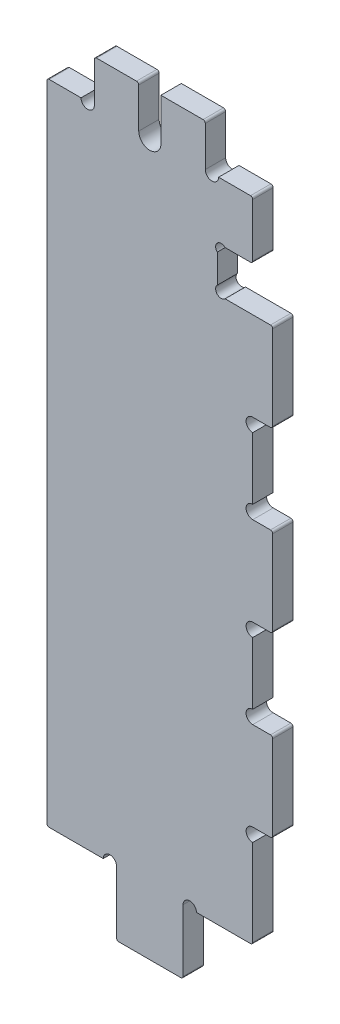
SolidWorks part; units mm, degrees
material "POM Acetal Copolymer"
ref_plane "Front Plane" through (0, 0, 0) normal (0, 0, 1) x (1, 0, 0)
ref_plane "Top Plane" through (0, 0, 0) normal (0, 1, 0) x (1, 0, 0)
ref_plane "Right Plane" through (0, 0, 0) normal (1, 0, 0) x (0, 0, -1)
sketch "Sketch1" plane through (0, 0, 0) normal (0, 0, 1) x (1, 0, 0)
  line L0 (10.7, 146) -> (10.7, 155.5)
  line L1 (0, 0) -> (15.7, 0)
  line L2 (0, 0) -> (0, 146)
  line L3 (0, 146) -> (10.7, 146)
  line L4 (46.4, 0) -> (46.4, 23)
  line L5 (10.7, 155.5) -> (20.7, 155.5)
  line L6 (20.7, 155.5) -> (20.7, 146)
  line L7 (20.7, 146) -> (25.7, 146)
  line L8 (10.7, 146) -> (20.7, 146) construction
  line L9 (23.2, -14.5) -> (23.2, 146) construction
  line L10 (15.7, 0) -> (15.7, -14.5)
  line L11 (15.7, -14.5) -> (30.7, -14.5)
  line L12 (30.7, -14.5) -> (30.7, 0)
  line L13 (30.7, 0) -> (46.4, 0)
  line L14 (15.7, 0) -> (30.7, 0) construction
  line L15 (35.7, 146) -> (25.7, 146) construction
  line L16 (25.7, 155.5) -> (25.7, 146)
  line L17 (35.7, 155.5) -> (25.7, 155.5)
  line L18 (35.7, 146) -> (35.7, 155.5)
  line L19 (35.7, 146) -> (46.4, 146)
  line L20 (46.4, 123) -> (50.9, 123)
  line L21 (50.9, 123) -> (50.9, 103)
  line L22 (50.9, 103) -> (46.4, 103)
  line L23 (46.4, 83) -> (50.9, 83)
  line L24 (50.9, 83) -> (50.9, 63)
  line L25 (50.9, 63) -> (46.4, 63)
  line L26 (46.4, 43) -> (50.9, 43)
  line L27 (50.9, 43) -> (50.9, 23)
  line L28 (50.9, 23) -> (46.4, 23)
  line L29 (46.4, 123) -> (46.4, 146)
  line L30 (46.4, 83) -> (46.4, 103)
  line L31 (46.4, 43) -> (46.4, 63)
  dimension "D1" = 46.4
  dimension "D2" = 146
  dimension "D3" = 14.5
  dimension "D4" = 15
  dimension "D5" = 10
  dimension "D6" = 5
  dimension "D7" = 9.5
  dimension "D8" = 20
  dimension "D9" = 23
  dimension "D10" = 20
  dimension "D11" = 20
  dimension "D12" = 23
  dimension "D13" = 4.5
extrude "Boss-Extrude1" add sketch "Sketch1" along normal blind 4.6
sketch "Sketch2" plane through (0, 0, 4.6) normal (0, 0, 1) x (1, 0, 0)
  line L0 (14.2, 0) -> (14.2, -5) construction
  line L1 (0, 0) -> (15.7, 0) construction
  line L2 (15.7, 0) -> (15.7, -5)
  line L3 (12.7, 0) -> (12.7, -5)
  line L4 (15.7, 0) -> (15.7, -14.5) construction
  line L5 (23.2, -14.5) -> (23.2, 146) construction
  line L6 (15.7, -14.5) -> (30.7, -14.5) construction
  line L8 (32.2, 0) -> (32.2, -5) construction
  line L9 (30.7, 0) -> (30.7, -5)
  line L10 (33.7, 0) -> (33.7, -5)
  line L11 (50.9, 33) -> (35.779, 33) construction
  line L12 (50.9, 23) -> (50.9, 43) construction
  line L13 (50.9, 73) -> (35.779, 73) construction
  line L14 (50.9, 63) -> (50.9, 83) construction
  line L15 (50.9, 113) -> (35.779, 113) construction
  line L16 (50.9, 103) -> (50.9, 123) construction
  line L17 (46.4, 21.5) -> (50.9, 21.5) construction
  line L18 (46.4, 0) -> (46.4, 23) construction
  line L19 (46.4, 23) -> (50.9, 23)
  line L20 (46.4, 20) -> (50.9, 20)
  line L21 (46.4, 61.5) -> (50.9, 61.5) construction
  line L22 (46.4, 43) -> (46.4, 63) construction
  line L23 (46.4, 63) -> (50.9, 63)
  line L24 (46.4, 60) -> (50.9, 60)
  line L25 (46.4, 101.5) -> (50.9, 101.5) construction
  line L26 (46.4, 83) -> (46.4, 103) construction
  line L27 (46.4, 103) -> (50.9, 103)
  line L28 (46.4, 100) -> (50.9, 100)
  line L29 (46.4, 23) -> (50.9, 23) construction
  line L30 (46.4, 44.5) -> (50.9, 44.5) construction
  line L31 (46.4, 43) -> (50.9, 43)
  line L32 (46.4, 46) -> (50.9, 46)
  line L33 (46.4, 84.5) -> (50.9, 84.5) construction
  line L34 (46.4, 83) -> (50.9, 83)
  line L35 (46.4, 86) -> (50.9, 86)
  line L39 (30.7, 155.5) -> (30.7, 144.8273) construction
  line L40 (35.7, 155.5) -> (25.7, 155.5) construction
  line L41 (37.2, 146) -> (37.2, 155.5) construction
  line L43 (35.7, 146) -> (35.7, 155.5)
  line L44 (38.7, 146) -> (38.7, 155.5)
  line L45 (35.7, 146) -> (35.7, 155.5) construction
  line L46 (23.2, 146) -> (23.2, 155.5) construction
  line L47 (25.7, 146) -> (25.7, 155.5)
  line L48 (20.7, 146) -> (20.7, 155.5)
  line L49 (9.2, 146) -> (9.2, 155.5) construction
  line L50 (10.7, 146) -> (10.7, 155.5)
  line L51 (7.7, 146) -> (7.7, 155.5)
  line L52 (20.7, 146) -> (20.7, 155.5) construction
  line L53 (25.7, 155.5) -> (25.7, 146) construction
  line L54 (20.7, 155.5) -> (10.7, 155.5) construction
  arc A0 (15.7, 0) -> (12.7, 0) centre (14.2, 0) ccw
  arc A1 (12.7, -5) -> (15.7, -5) centre (14.2, -5) ccw
  arc A2 (30.7, 0) -> (33.7, 0) centre (32.2, 0) cw
  arc A3 (33.7, -5) -> (30.7, -5) centre (32.2, -5) cw
  arc A4 (46.4, 23) -> (46.4, 20) centre (46.4, 21.5) ccw
  arc A5 (50.9, 20) -> (50.9, 23) centre (50.9, 21.5) ccw
  arc A6 (46.4, 63) -> (46.4, 60) centre (46.4, 61.5) ccw
  arc A7 (50.9, 60) -> (50.9, 63) centre (50.9, 61.5) ccw
  arc A8 (46.4, 103) -> (46.4, 100) centre (46.4, 101.5) ccw
  arc A9 (50.9, 100) -> (50.9, 103) centre (50.9, 101.5) ccw
  arc A10 (46.4, 43) -> (46.4, 46) centre (46.4, 44.5) cw
  arc A11 (50.9, 46) -> (50.9, 43) centre (50.9, 44.5) cw
  arc A12 (46.4, 83) -> (46.4, 86) centre (46.4, 84.5) cw
  arc A13 (50.9, 86) -> (50.9, 83) centre (50.9, 84.5) cw
  arc A16 (35.7, 146) -> (38.7, 146) centre (37.2, 146) ccw
  arc A17 (38.7, 155.5) -> (35.7, 155.5) centre (37.2, 155.5) ccw
  arc A18 (25.7, 146) -> (20.7, 146) centre (23.2, 146) cw
  arc A19 (20.7, 155.5) -> (25.7, 155.5) centre (23.2, 155.5) cw
  arc A20 (10.7, 146) -> (7.7, 146) centre (9.2, 146) cw
  arc A21 (7.7, 155.5) -> (10.7, 155.5) centre (9.2, 155.5) cw
  point P6 (14.2, -2.5)
  point P14 (48.65, 44.5)
  point P28 (32.2, -2.5)
  point P51 (48.65, 21.5)
  point P56 (48.65, 61.5)
  point P65 (48.65, 101.5)
  point P74 (48.65, 84.5)
  point P98 (37.2, 150.75)
  point P107 (23.2, 150.75)
  point P114 (9.2, 150.75)
  dimension "D1" = 3
  dimension "D2" = 5
  dimension "D3" = 9.5
  dimension "D4" = 9.5
extrude "Cut-Extrude1" cut sketch "Sketch2" against normal through all
sketch "Sketch8" plane through (0, 0, 0) normal (0, 0, -1) x (-1, 0, 0)
  line L1 (-46.4, 123) -> (-38.4, 123)
  line L2 (-46.4, 123) -> (-46.4, 133)
  line L3 (-46.4, 133) -> (-38.4, 133)
  line L4 (-38.4, 123) -> (-38.4, 133)
  dimension "D1" = 8
  dimension "D2" = 10
extrude "Cut-Extrude4" cut sketch "Sketch8" against normal blind 10
sketch "Sketch9" plane through (0, 0, 0) normal (0, 0, -1) x (-1, 0, 0)
  line L0 (-38.4, 123) -> (-38.4, 133) construction
  circle A0 centre (-39.28, 132.1123) radius 1.25
  circle A1 centre (-39.28, 123.8877) radius 1.25
  dimension "D3" = 2.5
  dimension "D4" = 2.5
  dimension "D1" = 0.88
  dimension "D2" = 0.88
extrude "Cut-Extrude5" cut sketch "Sketch9" against normal blind 10
fillet "Fillet1" radius 0.5 16 edges at (50.9, 43, 2.3) (50.9, 23, 2.3) (46.4, 0, 2.3) (30.7, -14.5, 2.3) (15.7, -14.5, 2.3) (0, 0, 2.3) (0, 146, 2.3) (10.7, 155.5, 2.3) (20.7, 155.5, 2.3) (35.7, 155.5, 2.3) (50.9, 83, 2.3) (50.9, 63, 2.3) (50.9, 103, 2.3) (46.4, 133, 2.3) (50.9, 123, 2.3) (46.4, 146, 2.3)
